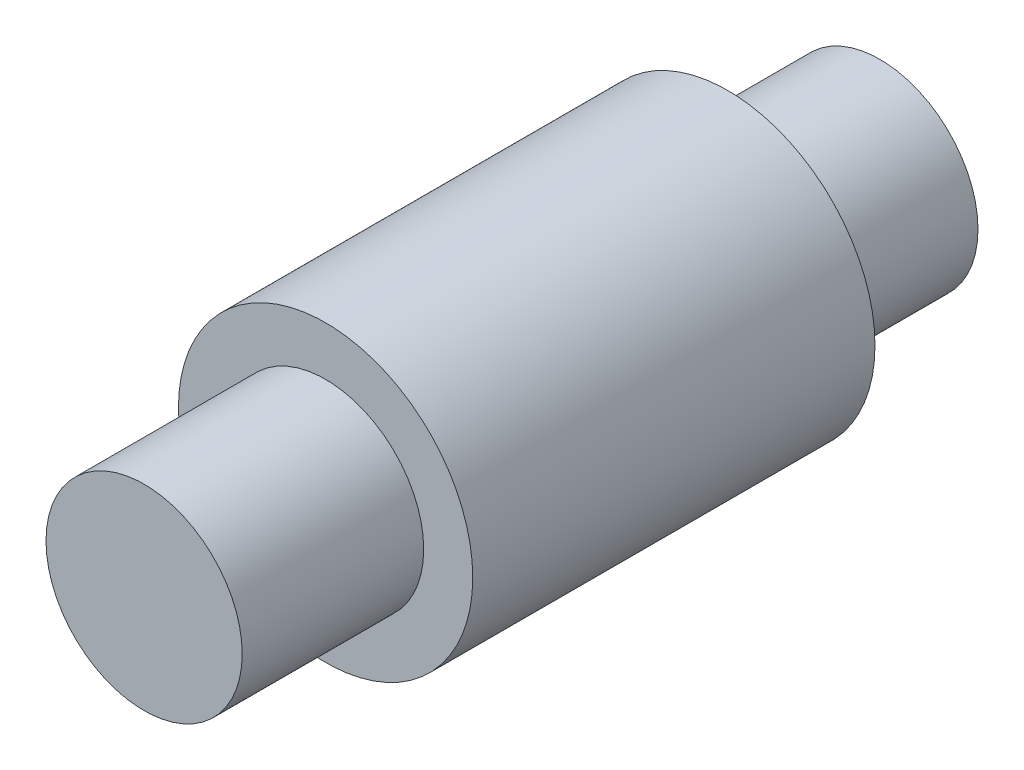
SolidWorks part; units mm, degrees
ref_plane "Front Plane" through (0, 0, 0) normal (0, 0, 1) x (1, 0, 0)
ref_plane "Top Plane" through (0, 0, 0) normal (0, 1, 0) x (1, 0, 0)
ref_plane "Right Plane" through (0, 0, 0) normal (1, 0, 0) x (0, 0, -1)
sketch "Sketch1" plane through (0, 0, 0) normal (0, 0, 1) x (1, 0, 0)
  circle A0 centre (0, 0) radius 15
  dimension "D1" = 30
extrude "Boss-Extrude1" add sketch "Sketch1" along normal blind 41
sketch "Sketch2" plane through (0, 0, 41) normal (0, 0, 1) x (1, 0, 0)
  circle A0 centre (0, 0) radius 10
  dimension "D1" = 20
extrude "Boss-Extrude2" add sketch "Sketch2" along normal blind 8.5
sketch "Sketch3" plane through (0, 0, 0) normal (0, 0, -1) x (-1, 0, 0)
  circle A0 centre (0, 0) radius 10
  dimension "D1" = 20
extrude "Boss-Extrude3" add sketch "Sketch3" along normal blind 5.5
sketch "Sketch4" plane through (0, 0, 49.5) normal (0, 0, 1) x (1, 0, 0)
  circle A0 centre (0, 0) radius 10
extrude "Boss-Extrude4" add sketch "Sketch4" along normal blind 10
sketch "Sketch5" plane through (0, 0, -5.5) normal (0, 0, -1) x (-1, 0, 0)
  circle A0 centre (0, 0) radius 10
extrude "Boss-Extrude5" add sketch "Sketch5" along normal blind 10
